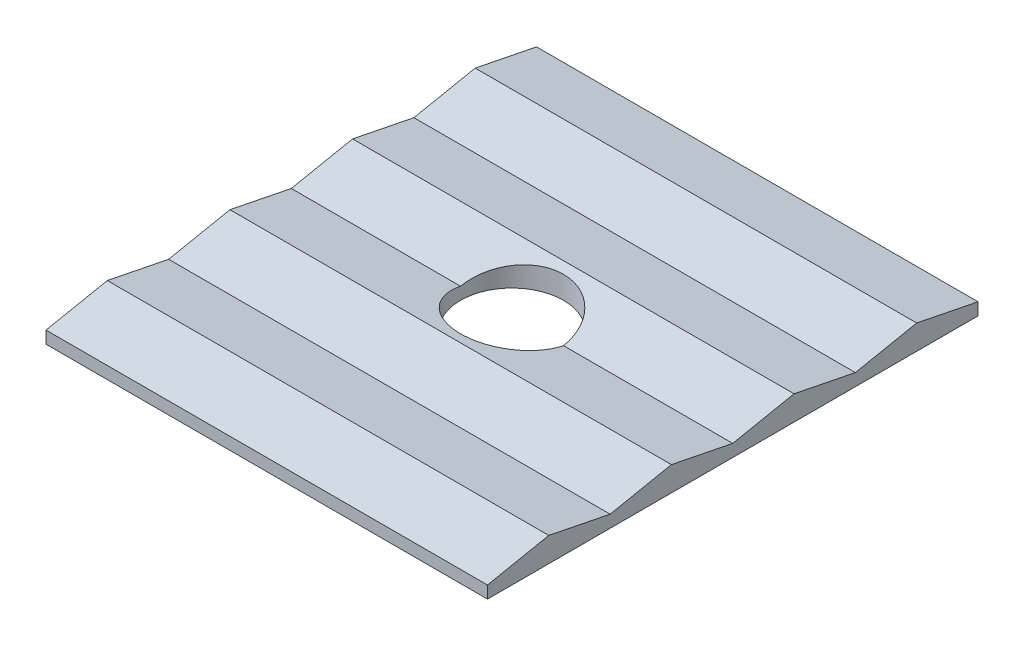
SolidWorks part; units mm, degrees
ref_plane "Front Plane" through (0, 0, 0) normal (0, 0, 1) x (1, 0, 0)
ref_plane "Top Plane" through (0, 0, 0) normal (0, 1, 0) x (1, 0, 0)
ref_plane "Right Plane" through (0, 0, 0) normal (1, 0, 0) x (0, 0, -1)
sketch "Sketch6" plane through (0, 0, 0) normal (1, 0, 0) x (0, 0, -1)
  line L0 (0, 0) -> (25.4, 0)
  line L1 (0, 0) -> (0, 0.635)
  line L9 (25.4, 0) -> (25.4, 0.635)
  line L10 (0, 0.635) -> (3.175, 1.27)
  line L11 (3.175, 1.27) -> (6.35, 0.635)
  line L12 (6.35, 0.635) -> (9.525, 1.27)
  line L13 (9.525, 1.27) -> (12.7, 0.635)
  line L14 (12.7, 0.635) -> (15.875, 1.27)
  line L15 (15.875, 1.27) -> (19.05, 0.635)
  line L16 (19.05, 0.635) -> (22.225, 1.27)
  line L17 (22.225, 1.27) -> (25.4, 0.635)
  line L19 (3.175, 0) -> (3.175, 1.27) [skipped]
  line L20 (6.35, 0) -> (6.35, 1.27) [skipped]
  line L21 (9.525, 0) -> (9.525, 1.27) [skipped]
  line L22 (12.7, 0) -> (12.7, 1.27) [skipped]
  line L23 (15.875, 0) -> (15.875, 1.27) [skipped]
  line L24 (19.05, 0) -> (19.05, 1.27) [skipped]
  line L25 (22.225, 0) -> (22.225, 1.27) [skipped]
  dimension "D3" = 9
  dimension "D1" = 25.4
extrude "Boss-Extrude1" add sketch "Sketch6" along normal blind 22.86
sketch "Sketch7" plane through (0, 0, 0) normal (0, -1, 0) x (1, 0, 0)
  line L0 (11.43, 0) -> (11.43, -25.4) construction
  line L1 (22.86, 0) -> (0, 0) construction
  line L2 (22.86, -25.4) -> (0, -25.4) construction
  circle A0 centre (11.43, -12.7) radius 2.667
  dimension "D1" = 5.334
extrude "Cut-Extrude1" cut sketch "Sketch7" against normal blind 22.86
